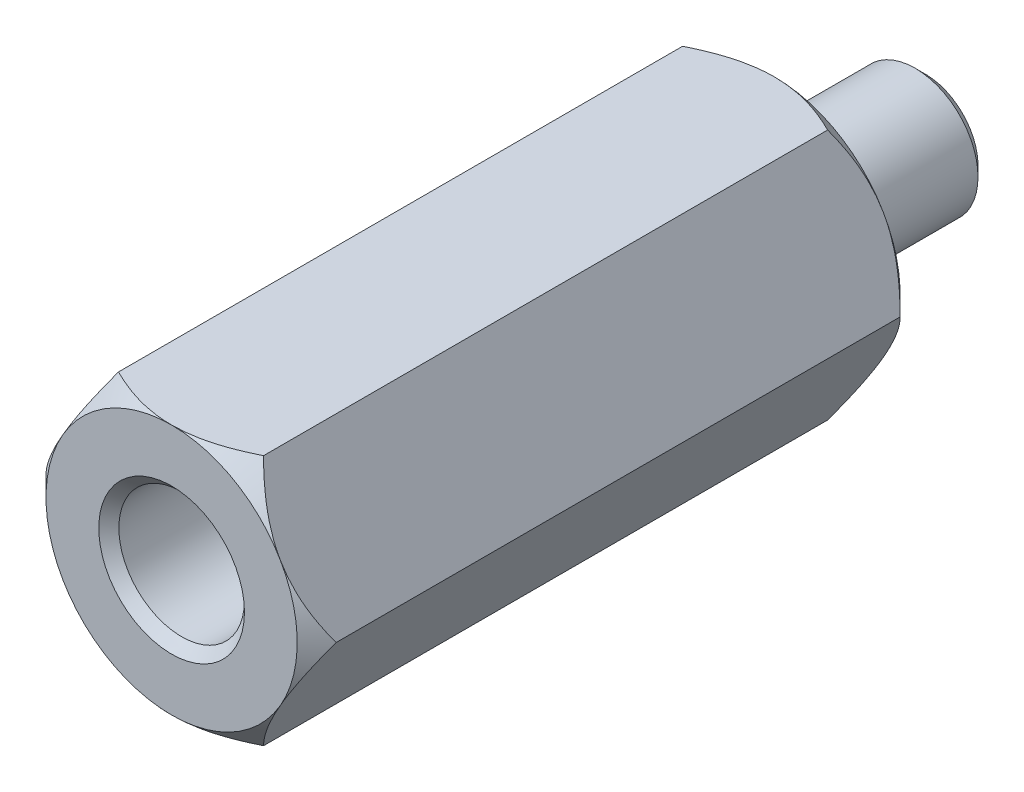
SolidWorks part; units mm, degrees
ref_plane "Plan de face" through (0, 0, 0) normal (0, 0, 1) x (1, 0, 0)
ref_plane "Plan de dessus" through (0, 0, 0) normal (0, 1, 0) x (1, 0, 0)
ref_plane "Plan de droite" through (0, 0, 0) normal (1, 0, 0) x (0, 0, -1)
sketch "Esquisse1" plane through (0, 0, 0) normal (0, 0, 1) x (1, 0, 0)
  line L1 (2.8868, 0) -> (1.4434, 2.5)
  line L2 (1.4434, 2.5) -> (-1.4434, 2.5)
  line L3 (-1.4434, 2.5) -> (-2.8868, 0)
  line L4 (-2.8868, 0) -> (-1.4434, -2.5)
  line L5 (-1.4434, -2.5) -> (1.4434, -2.5)
  line L6 (1.4434, -2.5) -> (2.8868, 0)
  circle A0 centre (0, 0) radius 2.5 construction
  dimension "D1" = 5
extrude "Boss.-Extru.1" add sketch "Esquisse1" along normal blind 12
sketch "Esquisse2" plane through (0, 0, 0) normal (0, 1, 0) x (1, 0, 0)
  line L0 (-1.5, 1) -> (-3, -0.5)
  line L1 (-3, 1) -> (-1.5, 1)
  line L2 (-3, 1) -> (-3, -0.5)
  line L3 (-3, -11.5) -> (-1.5, -13)
  line L4 (-1.5, -13) -> (-3, -13)
  line L5 (-3, -13) -> (-3, -11.5)
  line L6 (0, 0) -> (0, -12) construction
  line L7 (1.4434, 0) -> (-1.4434, 0) construction
  line L8 (1.4434, -12) -> (-1.4434, -12) construction
  dimension "D1" = 45
  dimension "D2" = 3
  dimension "D3" = 3
  dimension "D4" = 1
  dimension "D5" = 1
  dimension "D6" = 45
  dimension "D7" = 1.5
  dimension "D8" = 1.5
revolve "Enlèvement de matière-Révolution1" cut sketch "Esquisse2" angle 360 about L6
sketch "Esquisse3" plane through (0, 0, 12) normal (0, 0, 1) x (1, 0, 0)
  circle A0 centre (0, 0) radius 1.25
  dimension "D1" = 2.5
extrude "Enlèv. mat.-Extru.1" cut sketch "Esquisse3" against normal blind 6
chamfer "Chanfrein1" distance 0.2 angle 45 1 edges at (1.25, 0, 12)
sketch "Esquisse4" plane through (0, 0, 0) normal (0, 0, -1) x (-1, 0, 0)
  circle A0 centre (0, 0) radius 1.25
  dimension "D1" = 2.5
extrude "Boss.-Extru.2" add sketch "Esquisse4" along normal blind 3
chamfer "Chanfrein2" distance 0.2 angle 45 1 edges at (-1.25, 0, -3)
